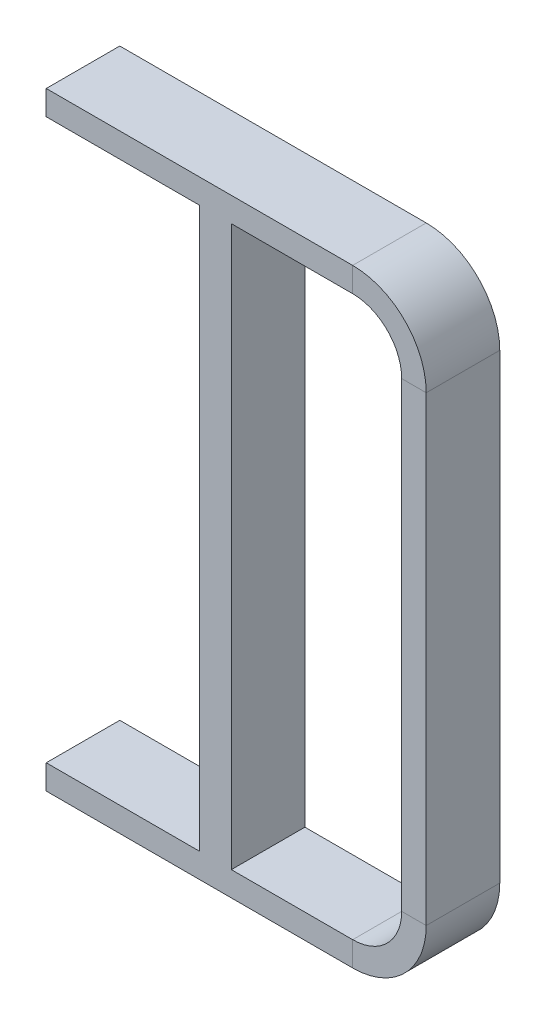
SolidWorks part; units mm, degrees
material "Cast Stainless Steel"
ref_plane "Front Plane" through (0, 0, 0) normal (0, 0, 1) x (1, 0, 0)
ref_plane "Top Plane" through (0, 0, 0) normal (0, 1, 0) x (1, 0, 0)
ref_plane "Right Plane" through (0, 0, 0) normal (1, 0, 0) x (0, 0, -1)
sketch "Sketch1" plane through (0, 0, 0) normal (0, 0, 1) x (1, 0, 0)
  line L0 (0, 0) -> (635, 0)
  line L1 (762, -127) -> (762, -1083.056)
  line L2 (635, -1210.056) -> (0, -1210.056)
  arc A0 (762, -1083.056) -> (635, -1210.056) centre (635, -1083.056) cw
  arc A1 (635, 0) -> (762, -127) centre (635, -127) cw
  point P7 (762, -1210.056)
  point P10 (762, 0)
  dimension "D3" = 127
  dimension "D1" = 1210.056
  dimension "D2" = 762
sketch "Sketch2" plane through (0, 0, 0) normal (1, 0, 0) x (0, 0, -1)
  line L1 (-76.2, 25.4) -> (76.2, 25.4)
  line L2 (-76.2, 25.4) -> (-76.2, -25.4)
  line L3 (-76.2, -25.4) -> (76.2, -25.4)
  line L4 (76.2, 25.4) -> (76.2, -25.4)
  line L5 (-76.2, 25.4) -> (76.2, -25.4) construction
  line L6 (-76.2, -25.4) -> (76.2, 25.4) construction
  point P0 (0, 0)
  dimension "D1" = 152.4
  dimension "D2" = 50.8
sweep "Sweep1" add profiles "Sketch2" path "Sketch1"
sketch "Sketch3" plane through (0, 25.4, 0) normal (0, 1, 0) x (1, 0, 0)
  line L0 (317.5, 76.2) -> (317.5, -76.2)
  line L1 (0, 76.2) -> (635, 76.2) construction
  line L2 (0, -76.2) -> (635, -76.2) construction
  line L3 (383.599, 76.2) -> (383.599, -76.2)
  line L4 (317.5, -76.2) -> (383.599, -76.2)
  line L5 (317.5, 76.2) -> (383.599, 76.2)
  line L6 (635, 76.2) -> (635, -76.2) construction
  dimension "D1" = 251.401
extrude "Boss-Extrude1" add sketch "Sketch3" against normal blind 1229.106
